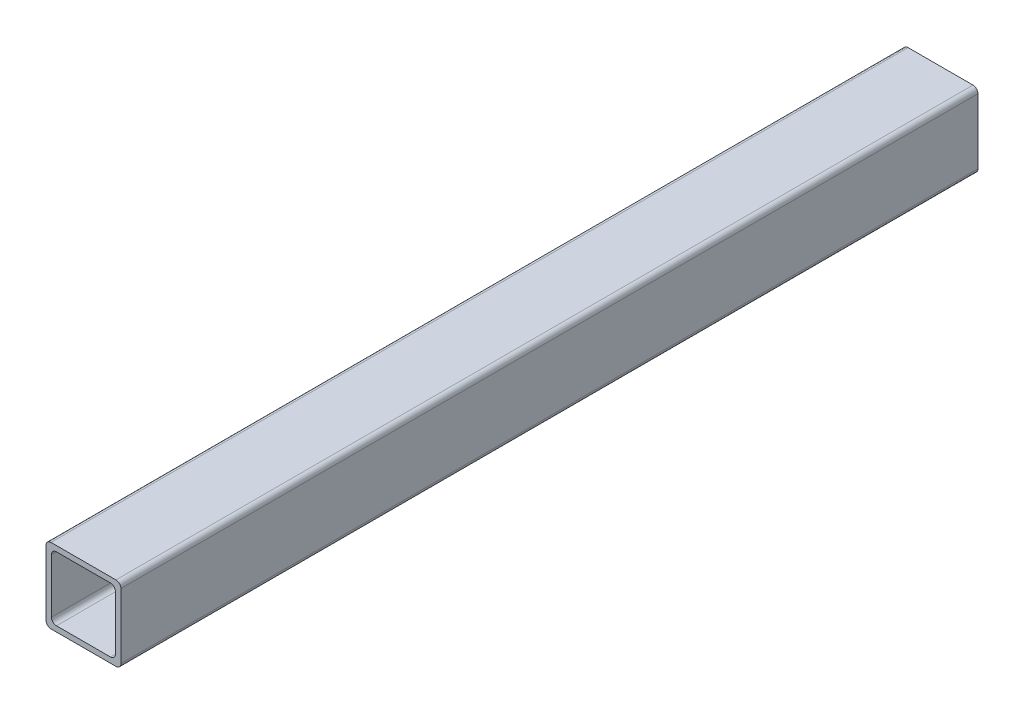
SolidWorks part; units mm, degrees
material "ASTM A500 Grade B Steel"
ref_plane "Front Plane" through (0, 0, 0) normal (0, 0, 1) x (1, 0, 0)
ref_plane "Top Plane" through (0, 0, 0) normal (0, 1, 0) x (1, 0, 0)
ref_plane "Right Plane" through (0, 0, 0) normal (1, 0, 0) x (0, 0, -1)
sketch "Sketch1" plane through (0, 0, 0) normal (0, 0, 1) x (1, 0, 0)
  line L0 (5.3086, -2.7686) -> (32.7914, -2.7686)
  line L1 (2.54, 0) -> (35.56, 0)
  line L2 (0, -2.54) -> (0, -35.56)
  line L3 (2.54, -38.1) -> (35.56, -38.1)
  line L4 (38.1, -2.54) -> (38.1, -35.56)
  line L5 (35.3314, -5.3086) -> (35.3314, -32.7914)
  line L6 (5.3086, -35.3314) -> (32.7914, -35.3314)
  line L7 (2.7686, -5.3086) -> (2.7686, -32.7914)
  line L8 (0, 0) -> (0, -38.1) construction
  line L9 (0, -38.1) -> (38.1, -38.1) construction
  line L10 (38.1, 0) -> (38.1, -38.1) construction
  line L11 (2.7686, -2.7686) -> (2.7686, -35.3314) construction
  line L12 (2.7686, -35.3314) -> (35.3314, -35.3314) construction
  line L13 (35.3314, -2.7686) -> (35.3314, -35.3314) construction
  line L14 (2.7686, -2.7686) -> (35.3314, -2.7686) construction
  line L15 (0, 0) -> (38.1, 0) construction
  arc A0 (0, -35.56) -> (2.54, -38.1) centre (2.54, -35.56) ccw
  arc A1 (38.1, -35.56) -> (35.56, -38.1) centre (35.56, -35.56) cw
  arc A2 (2.7686, -32.7914) -> (5.3086, -35.3314) centre (5.3086, -32.7914) ccw
  arc A3 (32.7914, -35.3314) -> (35.3314, -32.7914) centre (32.7914, -32.7914) ccw
  arc A4 (35.3314, -5.3086) -> (32.7914, -2.7686) centre (32.7914, -5.3086) ccw
  arc A5 (38.1, -2.54) -> (35.56, 0) centre (35.56, -2.54) ccw
  arc A6 (0, -2.54) -> (2.54, 0) centre (2.54, -2.54) cw
  arc A7 (5.3086, -2.7686) -> (2.7686, -5.3086) centre (5.3086, -5.3086) ccw
  point P12 (0, -38.1)
  dimension "D4" = 2.54
  dimension "D3" = 2.7686
extrude "Boss-Extrude1" add sketch "Sketch1" along normal blind 435.78
